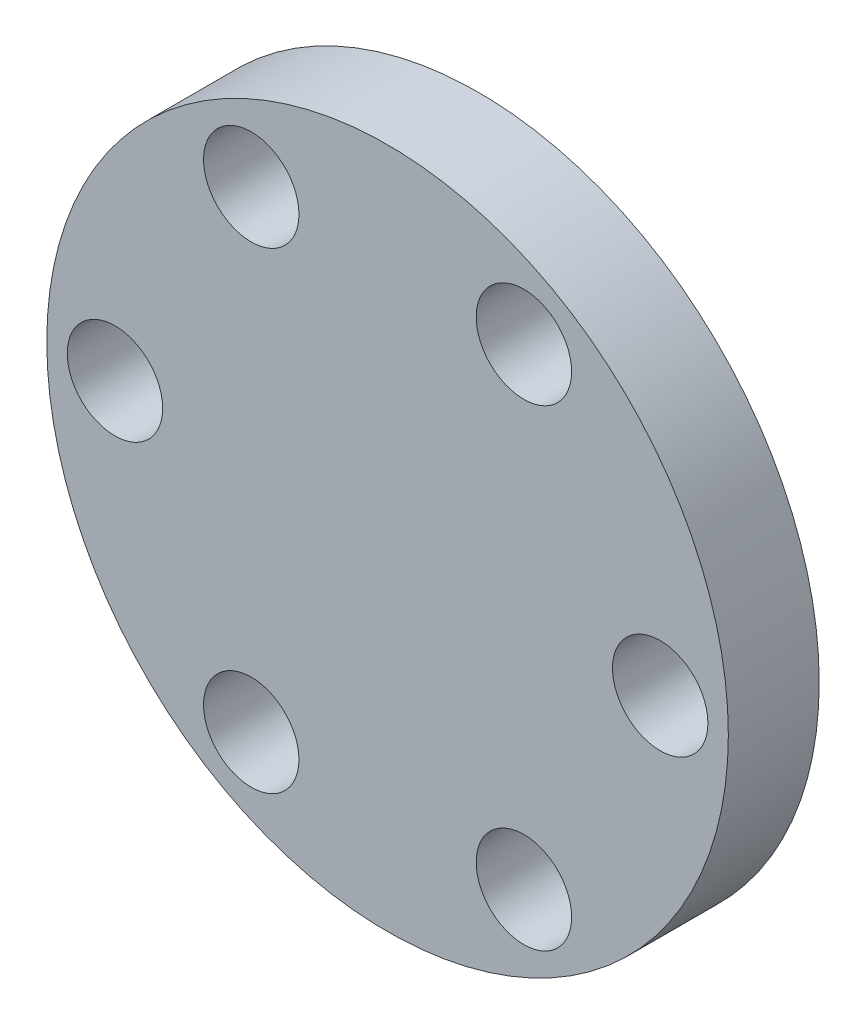
SolidWorks part; units mm, degrees
ref_plane "Front Plane" through (0, 0, 0) normal (1, 0, 0) x (0, 1, 0)
ref_plane "Top Plane" through (0, 0, 0) normal (0, 0, 1) x (0, 1, 0)
ref_plane "Right Plane" through (0, 0, 0) normal (0, 1, 0) x (-1, 0, 0)
sketch "Sketch1" plane through (0, 0, 0) normal (0, 0, 1) x (0, 1, 0)
  circle A0 centre (0, 0) radius 15
  circle A1 centre (0, 12) radius 2.1
  circle A2 centre (10.3923, 6) radius 2.1
  circle A3 centre (10.3923, -6) radius 2.1
  circle A4 centre (0, -12) radius 2.1
  circle A5 centre (-10.3923, -6) radius 2.1
  circle A6 centre (-10.3923, 6) radius 2.1
  point P6 (-11.9932, 7.5255)
  point P7 (0, 0)
  point P17 (0, 0)
  dimension "D1" = 30
  dimension "D2" = 4.2
  dimension "D3" = 12
  dimension "D4" = 6
extrude "Boss-Extrude1" add sketch "Sketch1" along normal mid plane 4
